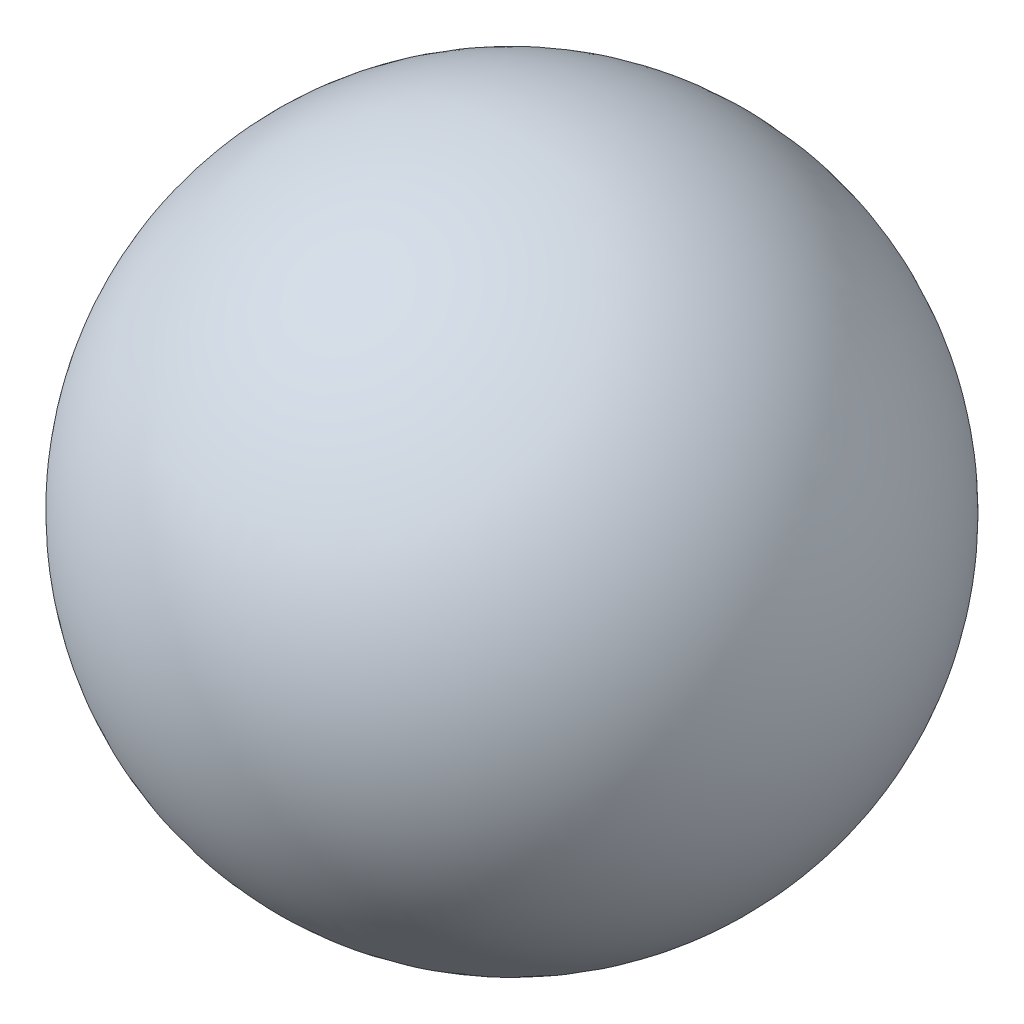
SolidWorks part; units mm, degrees
material "Plain Carbon Steel"
ref_plane "Front Plane" through (0, 0, 0) normal (0, 0, 1) x (1, 0, 0)
ref_plane "Top Plane" through (0, 0, 0) normal (0, 1, 0) x (1, 0, 0)
ref_plane "Right Plane" through (0, 0, 0) normal (1, 0, 0) x (0, 0, -1)
sketch "Sketch1" plane through (0, 0, 0) normal (0, 1, 0) x (1, 0, 0)
  line L0 (-31.748, 0.3553) -> (31.75, 0)
  arc A0 (31.75, 0) -> (-31.748, 0.3553) centre (0, 0) ccw
  point P5 (0, 0)
  dimension "D1" = 63.5
revolve "Revolve1" add sketch "Sketch1" angle 360 about L0
